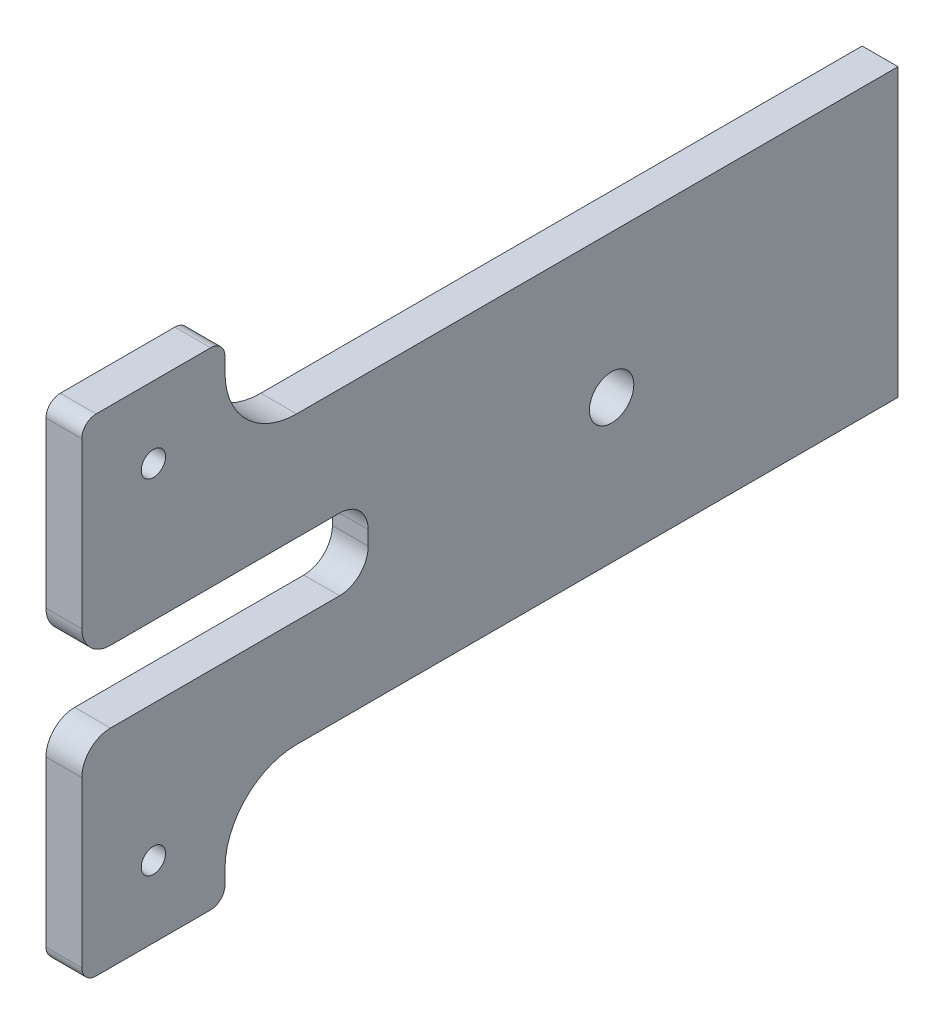
SolidWorks part; units mm, degrees
ref_plane "Front Plane" through (0, 0, 0) normal (1, 0, 0) x (0, 1, 0)
ref_plane "Top Plane" through (0, 0, 0) normal (0, 0, 1) x (0, 1, 0)
ref_plane "Right Plane" through (0, 0, 0) normal (0, 1, 0) x (-1, 0, 0)
sketch "Sketch2" plane through (0, 0, 0) normal (1, 0, 0) x (0, 1, 0)
  line L0 (-20, 0) -> (-20, 94)
  line L1 (-20, 0) -> (20, 0)
  line L5 (20, 0) -> (20, 94)
  line L7 (0, 114) -> (0, 0) construction
  line L9 (-34, 114) -> (-34, 94)
  line L10 (-34, 94) -> (-20, 94)
  line L11 (-34, 114) -> (34, 114)
  line L12 (20, 94) -> (34, 94)
  line L13 (34, 94) -> (34, 114)
  circle A0 centre (0, 40) radius 3.1
  circle A1 centre (-24, 104) radius 1.7
  circle A2 centre (24, 104) radius 1.7
  point P4 (0, 0)
  point P18 (0, 0)
  point P19 (0, 0)
  dimension "D3" = 40
  dimension "D4" = 6.2
  dimension "D11" = 3.4
  dimension "D1" = 68
  dimension "D2" = 40
  dimension "D5" = 20
  dimension "D6" = 14
  dimension "D7" = 114
  dimension "D8" = 48
  dimension "D9" = 24
  dimension "D10" = 64
extrude "Boss-Extrude1" add sketch "Sketch2" along normal blind 5
fillet "Fillet1" radius 10 2 edges at (2.5, -20, 94) (2.5, 20, 94)
fillet "Fillet2" radius 2 4 edges at (2.5, 34, 114) (2.5, 34, 94) (2.5, -34, 114) (2.5, -34, 94)
sketch "Sketch3" plane through (0, 0, 0) normal (-1, 0, 0) x (0, -1, 0)
  line L0 (0, 114) -> (0, 0) construction
  line L1 (-32, 114) -> (32, 114) construction
  line L3 (-5, 114) -> (5, 114)
  line L4 (-5, 114) -> (-5, 74)
  line L5 (-5, 74) -> (5, 74)
  line L6 (5, 114) -> (5, 74)
  point P9 (0, 0)
  point P10 (0, 0)
  point P11 (0, 114)
  dimension "D1" = 10
  dimension "D2" = 40
extrude "Cut-Extrude1" cut sketch "Sketch3" against normal blind 5
fillet "Fillet3" radius 4 4 edges at (2.5, -5, 114) (2.5, 5, 114) (2.5, -5, 74) (2.5, 5, 74)
equation "\"`0\"=9.98903"
